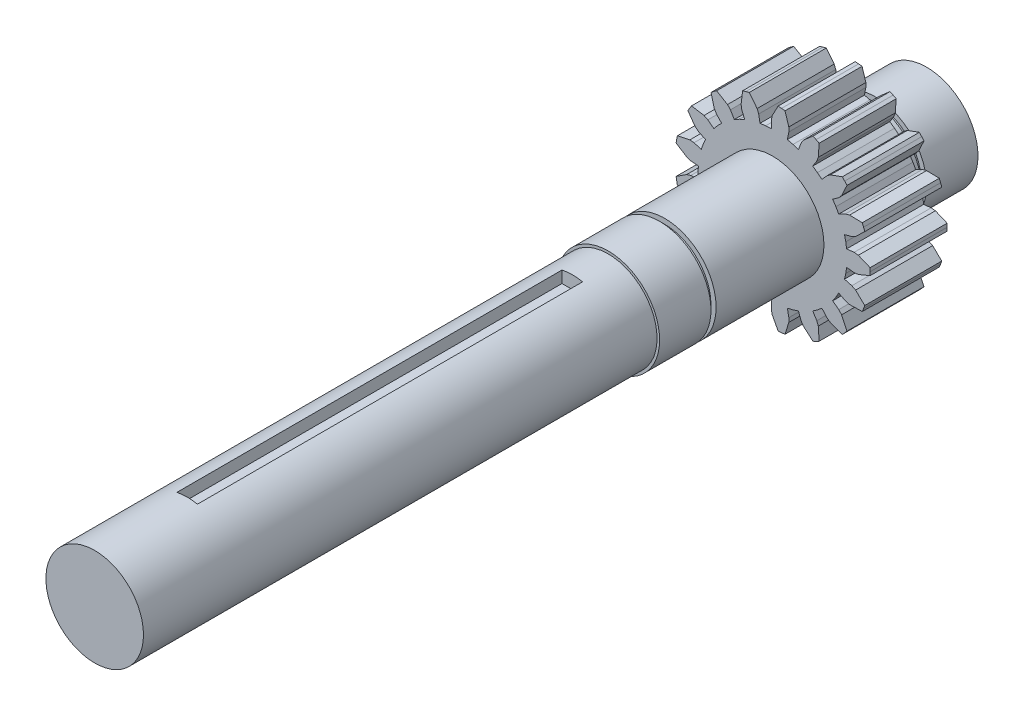
SolidWorks part; units mm, degrees
ref_plane "Front Plane" through (0, 0, 0) normal (0, 0, 1) x (1, 0, 0)
ref_plane "Top Plane" through (0, 0, 0) normal (0, 1, 0) x (1, 0, 0)
ref_plane "Right Plane" through (0, 0, 0) normal (1, 0, 0) x (0, 0, -1)
sketch "Sketch1" plane through (0, 0, 0) normal (0, 0, 1) x (1, 0, 0)
  line L0 (14.4166, -1.5529) -> (15.8829, -1.7109)
  line L1 (15.8829, -1.7109) -> (16.7037, -1.6224)
  line L2 (16.7037, -1.6224) -> (18.988, -0.6739)
  line L3 (18.988, -0.6739) -> (19, 0)
  line L4 (19, 0) -> (18.988, 0.6739)
  line L5 (18.988, 0.6739) -> (16.7037, 1.6224)
  line L6 (16.7037, 1.6224) -> (15.8829, 1.7109)
  line L7 (15.8829, 1.7109) -> (14.4166, 1.5529)
  line L8 (14.4166, 1.5529) -> (14.2531, 2.6644)
  line L9 (14.2531, 2.6644) -> (14.0041, 3.7598)
  line L10 (14.0041, 3.7598) -> (15.4284, 4.1422)
  line L11 (15.4284, 4.1422) -> (16.1618, 4.5212)
  line L12 (16.1618, 4.5212) -> (17.9493, 6.2308)
  line L13 (17.9493, 6.2308) -> (17.717, 6.8636)
  line L14 (17.717, 6.8636) -> (17.4624, 7.4877)
  line L15 (17.4624, 7.4877) -> (14.9896, 7.5469)
  line L16 (14.9896, 7.5469) -> (14.1923, 7.3329)
  line L17 (14.1923, 7.3329) -> (12.8821, 6.6559)
  line L18 (12.8821, 6.6559) -> (12.3281, 7.6333)
  line L19 (12.3281, 7.6333) -> (11.7002, 8.5648)
  line L20 (11.7002, 8.5648) -> (12.8902, 9.4359)
  line L21 (12.8902, 9.4359) -> (13.4372, 10.0542)
  line L22 (13.4372, 10.0542) -> (14.4864, 12.2941)
  line L23 (14.4864, 12.2941) -> (14.0412, 12.8002)
  line L24 (14.0412, 12.8002) -> (13.5783, 13.2902)
  line L25 (13.5783, 13.2902) -> (11.2512, 12.4522)
  line L26 (11.2512, 12.4522) -> (10.585, 11.9646)
  line L27 (10.585, 11.9646) -> (9.6078, 10.86)
  line L28 (9.6078, 10.86) -> (8.7382, 11.5712)
  line L29 (8.7382, 11.5712) -> (7.8162, 12.213)
  line L30 (7.8162, 12.213) -> (8.6111, 13.4552)
  line L31 (8.6111, 13.4552) -> (8.8978, 14.2294)
  line L32 (8.8978, 14.2294) -> (9.067, 16.697)
  line L33 (9.067, 16.697) -> (8.469, 17.0081)
  line L34 (8.469, 17.0081) -> (7.8604, 17.2978)
  line L35 (7.8604, 17.2978) -> (5.9932, 15.6757)
  line L36 (5.9932, 15.6757) -> (5.5481, 14.9804)
  line L37 (5.5481, 14.9804) -> (5.0359, 13.5974)
  line L38 (5.0359, 13.5974) -> (3.9681, 13.9465)
  line L39 (3.9681, 13.9465) -> (2.8765, 14.2118)
  line L40 (2.8765, 14.2118) -> (3.1691, 15.6573)
  line L41 (3.1691, 15.6573) -> (3.1567, 16.4827)
  line L42 (3.1567, 16.4827) -> (2.4231, 18.8449)
  line L43 (2.4231, 18.8449) -> (1.7531, 18.9189)
  line L44 (1.7531, 18.9189) -> (1.0809, 18.9692)
  line L45 (1.0809, 18.9692) -> (-0.0743, 16.7821)
  line L46 (-0.0743, 16.7821) -> (-0.2381, 15.973)
  line L47 (-0.2381, 15.973) -> (-0.2161, 14.4984)
  line L48 (-0.2161, 14.4984) -> (-1.3379, 14.4381)
  line L49 (-1.3379, 14.4381) -> (-2.4516, 14.2912)
  line L50 (-2.4516, 14.2912) -> (-2.701, 15.7448)
  line L51 (-2.701, 15.7448) -> (-3.0107, 16.51)
  line L52 (-3.0107, 16.51) -> (-4.5481, 18.4476)
  line L53 (-4.5481, 18.4476) -> (-5.1996, 18.2747)
  line L54 (-5.1996, 18.2747) -> (-5.8445, 18.0788)
  line L55 (-5.8445, 18.0788) -> (-6.1316, 15.622)
  line L56 (-6.1316, 15.622) -> (-5.9921, 14.8084)
  line L57 (-5.9921, 14.8084) -> (-5.4389, 13.4413)
  line L58 (-5.4389, 13.4413) -> (-6.4632, 12.9799)
  line L59 (-6.4632, 12.9799) -> (-7.4487, 12.4405)
  line L60 (-7.4487, 12.4405) -> (-8.2063, 13.7059)
  line L61 (-8.2063, 13.7059) -> (-8.7715, 14.3075)
  line L62 (-8.7715, 14.3075) -> (-10.905, 15.5589)
  line L63 (-10.905, 15.5589) -> (-11.4501, 15.1623)
  line L64 (-11.4501, 15.1623) -> (-11.9807, 14.7466)
  line L65 (-11.9807, 14.7466) -> (-11.3609, 12.3521)
  line L66 (-11.3609, 12.3521) -> (-10.9369, 11.6438)
  line L67 (-10.9369, 11.6438) -> (-9.9272, 10.5688)
  line L68 (-9.9272, 10.5688) -> (-10.7156, 9.7686)
  line L69 (-10.7156, 9.7686) -> (-11.4397, 8.9097)
  line L70 (-11.4397, 8.9097) -> (-12.6033, 9.8159)
  line L71 (-12.6033, 9.8159) -> (-13.3477, 10.1727)
  line L72 (-13.3477, 10.1727) -> (-15.7892, 10.5689)
  line L73 (-15.7892, 10.5689) -> (-16.1541, 10.0022)
  line L74 (-16.1541, 10.0022) -> (-16.4987, 9.4229)
  line L75 (-16.4987, 9.4229) -> (-15.0558, 7.414)
  line L76 (-15.0558, 7.414) -> (-14.4046, 6.9067)
  line L77 (-14.4046, 6.9067) -> (-13.0748, 6.269)
  line L78 (-13.0748, 6.269) -> (-13.5208, 5.238)
  line L79 (-13.5208, 5.238) -> (-13.8858, 4.1755)
  line L80 (-13.8858, 4.1755) -> (-15.2981, 4.6002)
  line L81 (-15.2981, 4.6002) -> (-16.1212, 4.6641)
  line L82 (-16.1212, 4.6641) -> (-18.5409, 4.1515)
  line L83 (-18.5409, 4.1515) -> (-18.6765, 3.4912)
  line L84 (-18.6765, 3.4912) -> (-18.7886, 2.8266)
  line L85 (-18.7886, 2.8266) -> (-16.7174, 1.4745)
  line L86 (-16.7174, 1.4745) -> (-15.9268, 1.2367)
  line L87 (-15.9268, 1.2367) -> (-14.4565, 1.1226)
  line L88 (-14.4565, 1.1226) -> (-14.5, 0)
  line L89 (-14.5, 0) -> (-14.4565, -1.1226)
  line L90 (-14.4565, -1.1226) -> (-15.9268, -1.2367)
  line L91 (-15.9268, -1.2367) -> (-16.7174, -1.4745)
  line L92 (-16.7174, -1.4745) -> (-18.7886, -2.8266)
  line L93 (-18.7886, -2.8266) -> (-18.6765, -3.4912)
  line L94 (-18.6765, -3.4912) -> (-18.5409, -4.1515)
  line L95 (-18.5409, -4.1515) -> (-16.1212, -4.6641)
  line L96 (-16.1212, -4.6641) -> (-15.2981, -4.6002)
  line L97 (-15.2981, -4.6002) -> (-13.8858, -4.1755)
  line L98 (-13.8858, -4.1755) -> (-13.5208, -5.238)
  line L99 (-13.5208, -5.238) -> (-13.0748, -6.269)
  line L100 (-13.0748, -6.269) -> (-14.4046, -6.9067)
  line L101 (-14.4046, -6.9067) -> (-15.0558, -7.414)
  line L102 (-15.0558, -7.414) -> (-16.4987, -9.4229)
  line L103 (-16.4987, -9.4229) -> (-16.1541, -10.0022)
  line L104 (-16.1541, -10.0022) -> (-15.7892, -10.5689)
  line L105 (-15.7892, -10.5689) -> (-13.3477, -10.1727)
  line L106 (-13.3477, -10.1727) -> (-12.6033, -9.8159)
  line L107 (-12.6033, -9.8159) -> (-11.4397, -8.9097)
  line L108 (-11.4397, -8.9097) -> (-10.7156, -9.7686)
  line L109 (-10.7156, -9.7686) -> (-9.9272, -10.5688)
  line L110 (-9.9272, -10.5688) -> (-10.9369, -11.6438)
  line L111 (-10.9369, -11.6438) -> (-11.3609, -12.3521)
  line L112 (-11.3609, -12.3521) -> (-11.9807, -14.7466)
  line L113 (-11.9807, -14.7466) -> (-11.4501, -15.1623)
  line L114 (-11.4501, -15.1623) -> (-10.905, -15.5589)
  line L115 (-10.905, -15.5589) -> (-8.7715, -14.3075)
  line L116 (-8.7715, -14.3075) -> (-8.2063, -13.7059)
  line L117 (-8.2063, -13.7059) -> (-7.4487, -12.4405)
  line L118 (-7.4487, -12.4405) -> (-6.4632, -12.9799)
  line L119 (-6.4632, -12.9799) -> (-5.4389, -13.4413)
  line L120 (-5.4389, -13.4413) -> (-5.9921, -14.8084)
  line L121 (-5.9921, -14.8084) -> (-6.1316, -15.622)
  line L122 (-6.1316, -15.622) -> (-5.8445, -18.0788)
  line L123 (-5.8445, -18.0788) -> (-5.1996, -18.2747)
  line L124 (-5.1996, -18.2747) -> (-4.5481, -18.4476)
  line L125 (-4.5481, -18.4476) -> (-3.0107, -16.51)
  line L126 (-3.0107, -16.51) -> (-2.701, -15.7448)
  line L127 (-2.701, -15.7448) -> (-2.4516, -14.2912)
  line L128 (-2.4516, -14.2912) -> (-1.3379, -14.4381)
  line L129 (-1.3379, -14.4381) -> (-0.2161, -14.4984)
  line L130 (-0.2161, -14.4984) -> (-0.2381, -15.973)
  line L131 (-0.2381, -15.973) -> (-0.0743, -16.7821)
  line L132 (-0.0743, -16.7821) -> (1.0809, -18.9692)
  line L133 (1.0809, -18.9692) -> (1.7531, -18.9189)
  line L134 (1.7531, -18.9189) -> (2.4231, -18.8449)
  line L135 (2.4231, -18.8449) -> (3.1567, -16.4827)
  line L136 (3.1567, -16.4827) -> (3.1691, -15.6573)
  line L137 (3.1691, -15.6573) -> (2.8765, -14.2118)
  line L138 (2.8765, -14.2118) -> (3.9681, -13.9465)
  line L139 (3.9681, -13.9465) -> (5.0359, -13.5974)
  line L140 (5.0359, -13.5974) -> (5.5481, -14.9804)
  line L141 (5.5481, -14.9804) -> (5.9932, -15.6757)
  line L142 (5.9932, -15.6757) -> (7.8604, -17.2978)
  line L143 (7.8604, -17.2978) -> (8.469, -17.0081)
  line L144 (8.469, -17.0081) -> (9.067, -16.697)
  line L145 (9.067, -16.697) -> (8.8978, -14.2294)
  line L146 (8.8978, -14.2294) -> (8.6111, -13.4552)
  line L147 (8.6111, -13.4552) -> (7.8162, -12.213)
  line L148 (7.8162, -12.213) -> (8.7382, -11.5712)
  line L149 (8.7382, -11.5712) -> (9.6078, -10.86)
  line L150 (9.6078, -10.86) -> (10.585, -11.9646)
  line L151 (10.585, -11.9646) -> (11.2512, -12.4522)
  line L152 (11.2512, -12.4522) -> (13.5783, -13.2902)
  line L153 (13.5783, -13.2902) -> (14.0412, -12.8002)
  line L154 (14.0412, -12.8002) -> (14.4864, -12.2941)
  line L155 (14.4864, -12.2941) -> (13.4372, -10.0542)
  line L156 (13.4372, -10.0542) -> (12.8902, -9.4359)
  line L157 (12.8902, -9.4359) -> (11.7002, -8.5648)
  line L158 (11.7002, -8.5648) -> (12.3281, -7.6333)
  line L159 (12.3281, -7.6333) -> (12.8821, -6.6559)
  line L160 (12.8821, -6.6559) -> (14.1923, -7.3329)
  line L161 (14.1923, -7.3329) -> (14.9896, -7.5469)
  line L162 (14.9896, -7.5469) -> (17.4624, -7.4877)
  line L163 (17.4624, -7.4877) -> (17.717, -6.8636)
  line L164 (17.717, -6.8636) -> (17.9493, -6.2308)
  line L165 (17.9493, -6.2308) -> (16.1618, -4.5212)
  line L166 (16.1618, -4.5212) -> (15.4284, -4.1422)
  line L167 (15.4284, -4.1422) -> (14.0041, -3.7598)
  line L168 (14.0041, -3.7598) -> (14.2531, -2.6644)
  line L169 (14.2531, -2.6644) -> (14.4166, -1.5529)
extrude "Gear_A_17T_Involute" add sketch "Sketch1" along normal blind 15
sketch "Sketch2" plane through (0, 0, 0) normal (0, 0, 1) x (1, 0, 0)
  circle A0 centre (0, 0) radius 10
extrude "Left_Stub_D20x15" add sketch "Sketch2" against normal blind 15
ref_plane "Plane_GearFace_15mm" through (0, 0, 15) normal (0, 0, 1) x (1, 0, 0)
sketch "Sketch3" plane through (0, 0, 15) normal (0, 0, 1) x (1, 0, 0)
  circle A0 centre (0, 0) radius 10
extrude "Right_Shaft_D20x32" add sketch "Sketch3" along normal blind 32
ref_plane "Plane_InputStart_47mm" through (0, 0, 47) normal (0, 0, 1) x (1, 0, 0)
sketch "Sketch4" plane through (0, 0, 47) normal (0, 0, 1) x (1, 0, 0)
  circle A0 centre (0, 0) radius 9.5
extrude "Input_Shaft_D19x100" add sketch "Sketch4" along normal blind 100
sketch "Sketch5" plane through (0, 0, 0) normal (1, 0, 0) x (0, 0, -1)
  line L1 (-54, 7) -> (-129, 7)
  line L2 (-54, 7) -> (-54, 11)
  line L3 (-54, 11) -> (-129, 11)
  line L4 (-129, 7) -> (-129, 11)
extrude "Keyway_Slot_75x4mm" cut sketch "Sketch5" against normal mid plane 4
sketch "Sketch6" plane through (0, 0, 0) normal (1, 0, 0) x (0, 0, -1)
  line L0 (-50, 0) -> (50, 0) construction
  line L2 (5, 9) -> (4, 9)
  line L3 (5, 9) -> (5, 11)
  line L4 (5, 11) -> (4, 11)
  line L5 (4, 9) -> (4, 11)
revolve "Left_SnapRing_Groove_D18" cut sketch "Sketch6" angle 360 about L0
sketch "Sketch7" plane through (0, 0, 0) normal (1, 0, 0) x (0, 0, -1)
  line L0 (-50, 0) -> (50, 0) construction
  line L2 (-36, 9) -> (-37, 9)
  line L3 (-36, 9) -> (-36, 11)
  line L4 (-36, 11) -> (-37, 11)
  line L5 (-37, 9) -> (-37, 11)
revolve "Right_SnapRing_Groove_D18" cut sketch "Sketch7" angle 360 about L0
